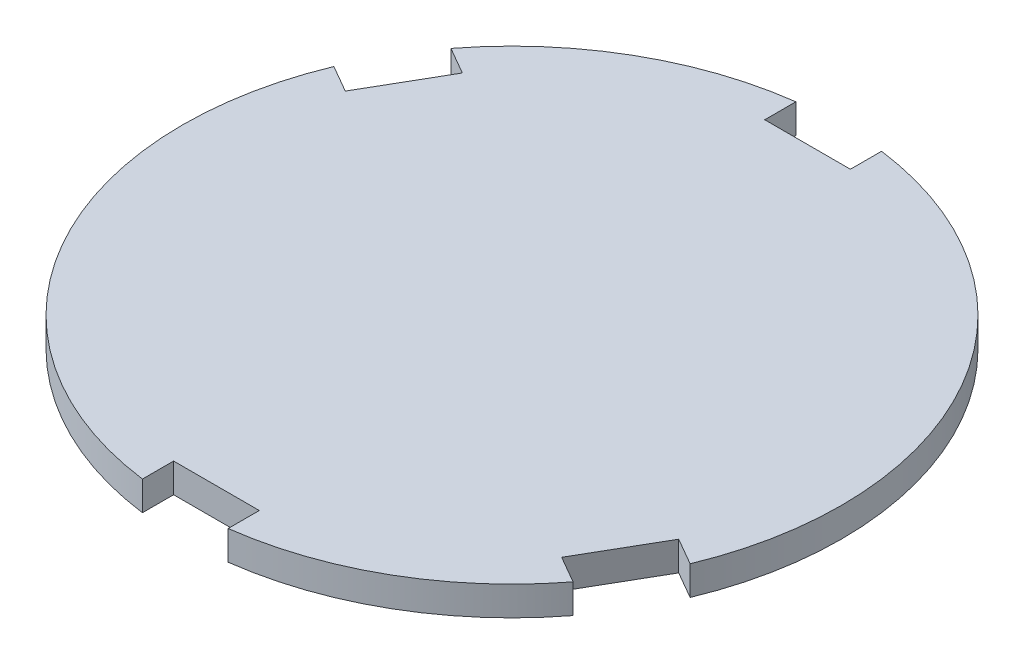
SolidWorks part; units mm, degrees
material "6061-T6 (SS)"
ref_plane "Front Plane" through (0, 0, 0) normal (0, 0, 1) x (1, 0, 0)
ref_plane "Top Plane" through (0, 0, 0) normal (0, 1, 0) x (1, 0, 0)
ref_plane "Right Plane" through (0, 0, 0) normal (1, 0, 0) x (0, 0, -1)
sketch "Sketch1" plane through (0, 0, 0) normal (0, 1, 0) x (1, 0, 0)
  circle A0 centre (0, 0) radius 53.721
  dimension "D1" = 107.442
extrude "Boss-Extrude1" add sketch "Sketch1" along normal blind 4.7625
sketch "Sketch2" plane through (0, 4.7625, 0) normal (0, 1, 0) x (1, 0, 0)
  line L0 (0, 0) -> (0, -55.3983) construction
  line L1 (0, 0) -> (71.6465, 0) construction
  line L2 (-6.985, -48.185) -> (6.985, -48.185)
  line L3 (-6.985, -48.185) -> (-6.985, -53.265)
  line L4 (6.985, -48.185) -> (6.985, -53.265)
  line L5 (6.985, 48.185) -> (6.985, 53.265)
  line L6 (-6.985, 48.185) -> (-6.985, 53.265)
  line L7 (-6.985, 48.185) -> (6.985, 48.185)
  circle A0 centre (0, 0) radius 53.721 construction
  arc A1 (-6.985, -53.265) -> (6.985, -53.265) centre (0, 0) ccw
  arc A2 (-6.985, 53.265) -> (6.985, 53.265) centre (0, 0) cw
  point P7 (0, -48.185)
  dimension "D1" = 5.08
  dimension "D2" = 13.97
extrude "Cut-Extrude1" cut sketch "Sketch2" against normal up to next
sketch "Sketch3" plane through (0, 4.7625, 0) normal (0, 1, 0) x (1, 0, 0)
  line L0 (0, 0) -> (40.5333, -23.4019) construction
  line L1 (0, -55) -> (0, 55) construction
  line L2 (0, 0) -> (26.8979, 46.5885) construction
  line L3 (38.2369, -30.1417) -> (45.2219, -18.0433)
  line L4 (38.2369, -30.1417) -> (42.6363, -32.6817)
  line L5 (45.2219, -18.0433) -> (49.6213, -20.5833)
  line L6 (-45.2219, 18.0433) -> (-49.6213, 20.5833)
  line L7 (-38.2369, 30.1417) -> (-42.6363, 32.6817)
  line L8 (-45.2219, 18.0433) -> (-38.2369, 30.1417)
  arc A0 (6.985, -53.265) -> (6.985, 53.265) centre (0, 0) ccw construction
  arc A1 (42.6363, -32.6817) -> (49.6213, -20.5833) centre (0, 0) ccw
  arc A2 (-49.6213, 20.5833) -> (-42.6363, 32.6817) centre (0, 0) cw
  point P9 (41.7294, -24.0925)
  dimension "D1" = 60
  dimension "D2" = 13.97
  dimension "D3" = 5.08
extrude "Cut-Extrude2" cut sketch "Sketch3" against normal up to next
